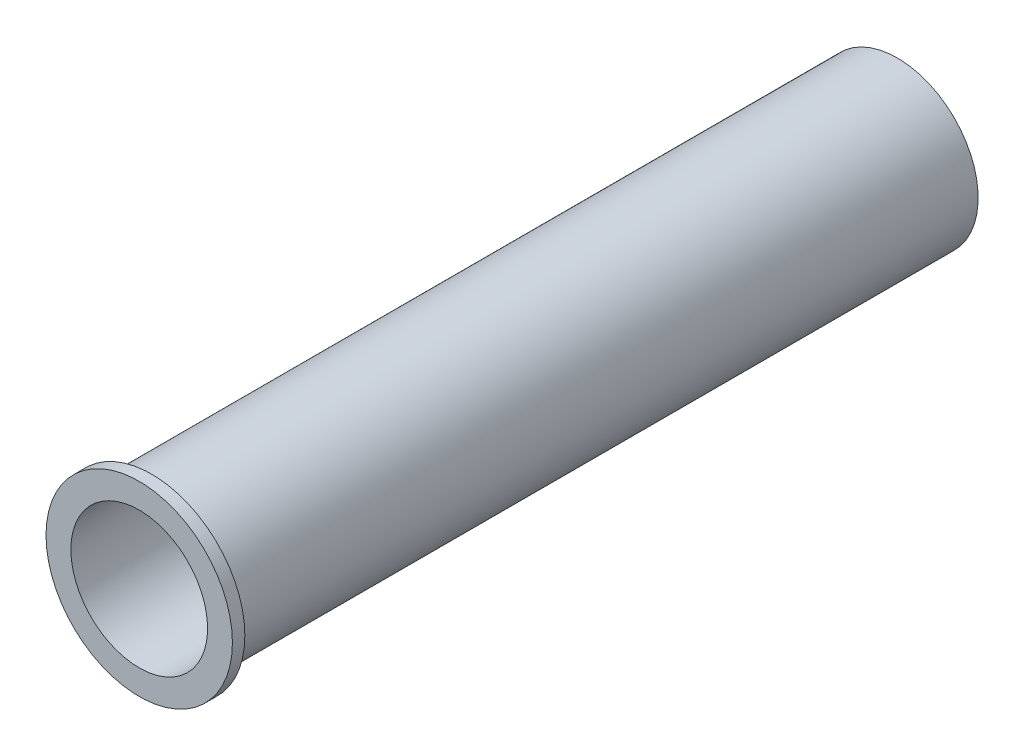
SolidWorks part; units mm, degrees
ref_plane "Alzado" through (0, 0, 0) normal (1, 0, 0) x (0, 1, 0)
ref_plane "Planta" through (0, 0, 0) normal (0, 0, 1) x (0, 1, 0)
ref_plane "Vista lateral" through (0, 0, 0) normal (0, 1, 0) x (-1, 0, 0)
sketch "Croquis1" plane through (0, 0, 0) normal (1, 0, 0) x (0, 1, 0)
  line L0 (11, -60) -> (11, 60)
  line L1 (11, 60) -> (15, 60)
  line L2 (15, 60) -> (15, 58)
  line L3 (15, 58) -> (13, 58)
  line L4 (13, 58) -> (13, -62)
  line L5 (13, -62) -> (9.5, -62)
  line L6 (9.5, -62) -> (9.5, -60)
  line L7 (9.5, -60) -> (11, -60)
  line L8 (0, 0) -> (0, 4.1277) construction
  point P3 (11, 0)
  dimension "D1" = 2
  dimension "D2" = 1.5
  dimension "D3" = 2
  dimension "D4" = 2
  dimension "D5" = 2
  dimension "D6" = 30
  dimension "D7" = 120
revolve "Revolución1" add sketch "Croquis1" angle 360 about L8
equation "\"D4@Croquis1\"=\"D3@Croquis1\""
equation "\"D5@Croquis1\"=\"D3@Croquis1\""
